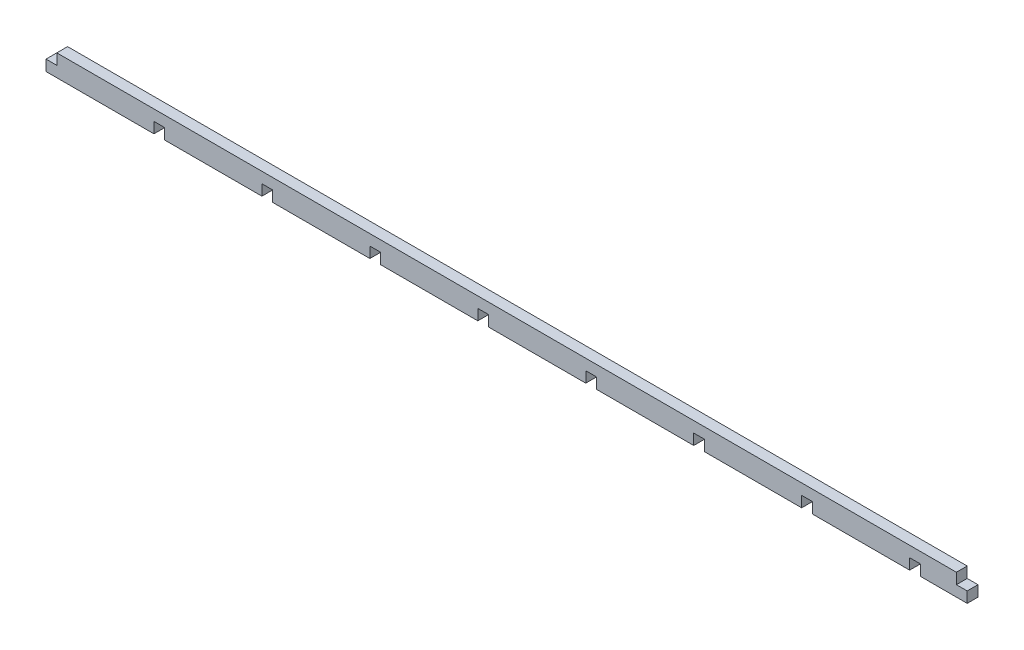
SolidWorks part; units mm, degrees
ref_plane "Front Plane" through (0, 0, 0) normal (0, 0, 1) x (1, 0, 0)
ref_plane "Top Plane" through (0, 0, 0) normal (0, 1, 0) x (1, 0, 0)
ref_plane "Right Plane" through (0, 0, 0) normal (1, 0, 0) x (0, 0, -1)
sketch "Sketch1" plane through (0, 0, 0) normal (0, 0, 1) x (1, 0, 0)
  line L0 (-39.1131, 50.2449) -> (-39.1131, 59.2865) construction
  line L1 (-159.1131, 67.7449) -> (-129.1131, 67.7449)
  line L2 (-159.1131, 67.7449) -> (-159.1131, 57.7449)
  line L3 (-159.1131, 50.2449) -> (80.8869, 50.2449)
  line L4 (80.8869, 67.7449) -> (80.8869, 57.7449)
  line L5 (-159.1131, 57.7449) -> (-162.1131, 57.7449)
  line L7 (-159.1131, 52.7449) -> (-162.1131, 52.7449)
  line L8 (-162.1131, 57.7449) -> (-162.1131, 52.7449)
  line L10 (-129.1131, 67.7449) -> (-129.1131, 60.2449)
  line L11 (-129.1131, 60.2449) -> (-126.1131, 60.2449)
  line L12 (-126.1131, 67.7449) -> (-126.1131, 60.2449)
  line L13 (80.8869, 52.7449) -> (83.8869, 52.7449)
  line L14 (83.8869, 57.7449) -> (83.8869, 52.7449)
  line L15 (80.8869, 57.7449) -> (83.8869, 57.7449)
  line L17 (-99.1131, 67.7449) -> (-99.1131, 60.2449)
  line L19 (-96.1131, 67.7449) -> (-96.1131, 60.2449)
  line L20 (-99.1131, 60.2449) -> (-96.1131, 60.2449)
  line L21 (-69.1131, 67.7449) -> (-69.1131, 60.2449)
  line L23 (-66.1131, 67.7449) -> (-66.1131, 60.2449)
  line L24 (-69.1131, 60.2449) -> (-66.1131, 60.2449)
  line L25 (-39.1131, 67.7449) -> (-39.1131, 60.2449)
  line L27 (-36.1131, 67.7449) -> (-36.1131, 60.2449)
  line L28 (-39.1131, 60.2449) -> (-36.1131, 60.2449)
  line L29 (-9.1131, 67.7449) -> (-9.1131, 60.2449)
  line L31 (-6.1131, 67.7449) -> (-6.1131, 60.2449)
  line L32 (-9.1131, 60.2449) -> (-6.1131, 60.2449)
  line L33 (20.8869, 67.7449) -> (20.8869, 60.2449)
  line L35 (23.8869, 67.7449) -> (23.8869, 60.2449)
  line L36 (20.8869, 60.2449) -> (23.8869, 60.2449)
  line L37 (50.8869, 67.7449) -> (50.8869, 60.2449)
  line L39 (53.8869, 67.7449) -> (53.8869, 60.2449)
  line L40 (50.8869, 60.2449) -> (53.8869, 60.2449)
  line L41 (-126.1131, 67.7449) -> (-99.1131, 67.7449)
  line L42 (-96.1131, 67.7449) -> (-69.1131, 67.7449)
  line L43 (-66.1131, 67.7449) -> (-39.1131, 67.7449)
  line L44 (-36.1131, 67.7449) -> (-9.1131, 67.7449)
  line L45 (-6.1131, 67.7449) -> (20.8869, 67.7449)
  line L46 (53.8869, 67.7449) -> (80.8869, 67.7449)
  line L47 (80.8869, 52.7449) -> (80.8869, 50.2449)
  line L48 (-159.1131, 52.7449) -> (-159.1131, 50.2449)
  line L49 (23.8869, 67.7449) -> (50.8869, 67.7449)
  dimension "D1" = 240
  dimension "D2" = 17.5
  dimension "D3" = 5
  dimension "D4" = 10
  dimension "D5" = 3
  dimension "D6" = 30
  dimension "D7" = 3
  dimension "D8" = 7.5
  dimension "D10" = 27
  dimension "D9" = 7
sketch "Sketch2" plane through (0, 0, 0) normal (0, 0, 1) x (1, 0, 0)
  line L0 (-107.1131, 64.7449) -> (-107.1131, 61.7449)
  line L1 (-164.1131, 67.7449) -> (85.8869, 67.7449)
  line L2 (-164.1131, 67.7449) -> (-164.1131, 64.7449)
  line L3 (-164.1131, 61.7449) -> (-137.1131, 61.7449)
  line L4 (85.8869, 67.7449) -> (85.8869, 64.7449)
  line L5 (-164.1131, 61.7449) -> (-167.1131, 61.7449)
  line L7 (-164.1131, 64.7449) -> (-167.1131, 64.7449)
  line L8 (-167.1131, 61.7449) -> (-167.1131, 64.7449)
  line L9 (-137.1131, 64.7449) -> (-134.1131, 64.7449)
  line L10 (-137.1131, 64.7449) -> (-137.1131, 61.7449)
  line L12 (-134.1131, 64.7449) -> (-134.1131, 61.7449)
  line L13 (-107.1131, 64.7449) -> (-104.1131, 64.7449)
  line L14 (-104.1131, 64.7449) -> (-104.1131, 61.7449)
  line L16 (-77.1131, 64.7449) -> (-77.1131, 61.7449)
  line L17 (-77.1131, 64.7449) -> (-74.1131, 64.7449)
  line L18 (-74.1131, 64.7449) -> (-74.1131, 61.7449)
  line L20 (-47.1131, 64.7449) -> (-47.1131, 61.7449)
  line L21 (-47.1131, 64.7449) -> (-44.1131, 64.7449)
  line L22 (-44.1131, 64.7449) -> (-44.1131, 61.7449)
  line L24 (-17.1131, 64.7449) -> (-17.1131, 61.7449)
  line L25 (-17.1131, 64.7449) -> (-14.1131, 64.7449)
  line L26 (-14.1131, 64.7449) -> (-14.1131, 61.7449)
  line L28 (12.8869, 64.7449) -> (12.8869, 61.7449)
  line L29 (12.8869, 64.7449) -> (15.8869, 64.7449)
  line L30 (15.8869, 64.7449) -> (15.8869, 61.7449)
  line L32 (42.8869, 64.7449) -> (42.8869, 61.7449)
  line L33 (42.8869, 64.7449) -> (45.8869, 64.7449)
  line L34 (45.8869, 64.7449) -> (45.8869, 61.7449)
  line L36 (-39.1131, 67.7449) -> (-39.1131, 91.4798) construction
  line L42 (-134.1131, 61.7449) -> (-107.1131, 61.7449)
  line L43 (-104.1131, 61.7449) -> (-77.1131, 61.7449)
  line L44 (-74.1131, 61.7449) -> (-47.1131, 61.7449)
  line L45 (-44.1131, 61.7449) -> (-17.1131, 61.7449)
  line L46 (-14.1131, 61.7449) -> (12.8869, 61.7449)
  line L47 (15.8869, 61.7449) -> (42.8869, 61.7449)
  line L48 (45.8869, 61.7449) -> (72.8869, 61.7449)
  line L49 (85.8869, 61.7449) -> (88.8869, 61.7449)
  line L50 (88.8869, 61.7449) -> (88.8869, 64.7449)
  line L51 (85.8869, 64.7449) -> (88.8869, 64.7449)
  line L53 (72.8869, 64.7449) -> (72.8869, 61.7449)
  line L54 (72.8869, 64.7449) -> (75.8869, 64.7449)
  line L55 (75.8869, 64.7449) -> (75.8869, 61.7449)
  line L56 (75.8869, 61.7449) -> (85.8869, 61.7449)
  point P16 (0, 0)
  dimension "D1" = 250
  dimension "D2" = 3
  dimension "D4" = 3
  dimension "D5" = 3
  dimension "D6" = 27
  dimension "D7" = 3
  dimension "D8" = 3
  dimension "D10" = 27
  dimension "D9" = 8
extrude "Boss-Extrude2" add sketch "Sketch2" along normal blind 3
equation "\"2ю7\"=2.7"
